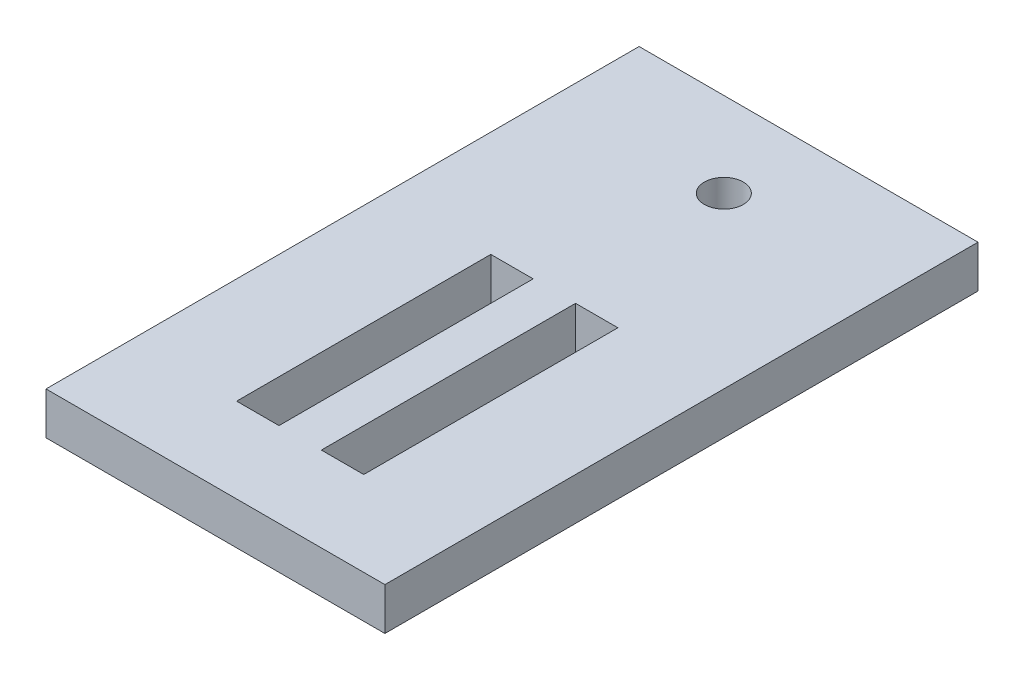
SolidWorks part; units mm, degrees
ref_plane "Front Plane" through (0, 0, 0) normal (0, 0, 1) x (1, 0, 0)
ref_plane "Top Plane" through (0, 0, 0) normal (0, 1, 0) x (1, 0, 0)
ref_plane "Right Plane" through (0, 0, 0) normal (1, 0, 0) x (0, 0, -1)
sketch "Sketch1" plane through (0, 0, 0) normal (0, 1, 0) x (1, 0, 0)
  line L1 (0, 0) -> (25.4, 0)
  line L2 (0, 0) -> (0, 44.45)
  line L3 (0, 44.45) -> (25.4, 44.45)
  line L4 (25.4, 0) -> (25.4, 44.45)
  line L5 (7.9375, 6.35) -> (11.1125, 6.35)
  line L6 (7.9375, 6.35) -> (7.9375, 25.4)
  line L7 (7.9375, 25.4) -> (11.1125, 25.4)
  line L8 (11.1125, 6.35) -> (11.1125, 25.4)
  line L9 (14.2875, 6.35) -> (17.4625, 6.35)
  line L10 (14.2875, 6.35) -> (14.2875, 25.4)
  line L11 (14.2875, 25.4) -> (17.4625, 25.4)
  line L12 (17.4625, 6.35) -> (17.4625, 25.4)
  circle A0 centre (12.7, 38.1) radius 1.4605
  dimension "D5" = 2.921
  dimension "D1" = 25.4
  dimension "D2" = 44.45
  dimension "D3" = 6.35
  dimension "D4" = 12.7
  dimension "D6" = 3.175
  dimension "D7" = 19.05
  dimension "D8" = 6.35
  dimension "D9" = 3.175
  dimension "D10" = 19.05
  dimension "D11" = 6.35
  dimension "D12" = 3.175
  dimension "D13" = 7.9375
extrude "Boss-Extrude1" add sketch "Sketch1" along normal blind 3.175
